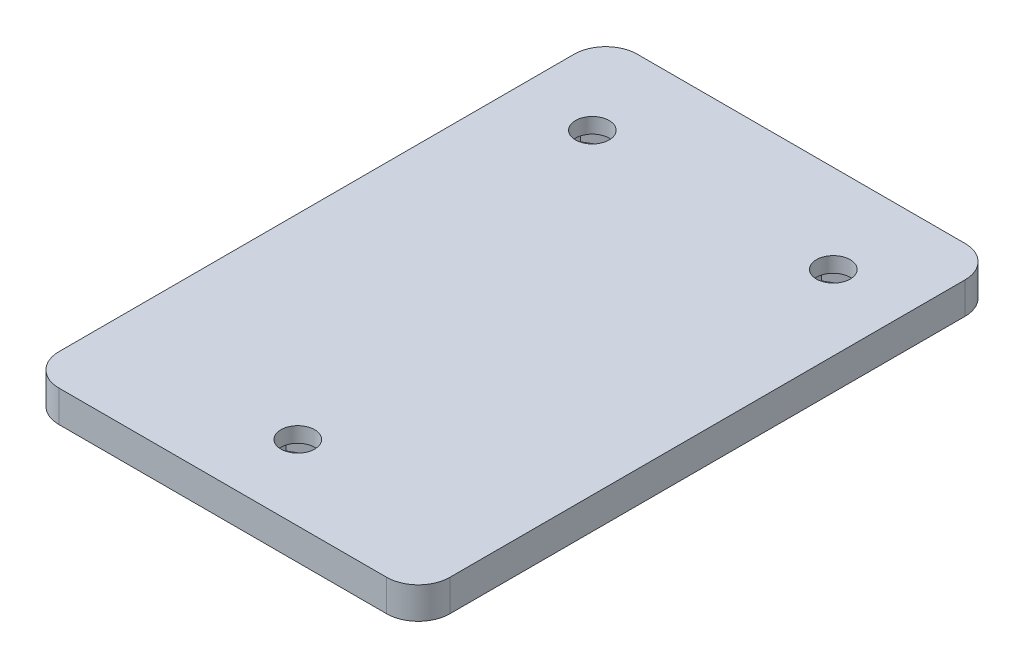
SolidWorks part; units mm, degrees
ref_plane "Front Plane" through (0, 0, 0) normal (0, 0, 1) x (1, 0, 0)
ref_plane "Top Plane" through (0, 0, 0) normal (0, 1, 0) x (1, 0, 0)
ref_plane "Right Plane" through (0, 0, 0) normal (1, 0, 0) x (0, 0, -1)
sketch "Sketch1" plane through (0, 0, 0) normal (0, 1, 0) x (1, 0, 0)
  line L1 (0, 0) -> (30.48, 0) construction
  line L2 (0, 0) -> (0, 48.26) construction
  line L3 (0, 48.26) -> (30.48, 48.26) construction
  line L4 (30.48, 0) -> (30.48, 48.26) construction
  line L8 (-0.3, -0.3) -> (-0.3, 48.56)
  line L9 (-0.3, 48.56) -> (30.78, 48.56)
  line L10 (30.78, -0.3) -> (30.78, 48.56)
  line L11 (-0.3, -0.3) -> (30.78, -0.3)
  line L12 (-3.3, -0.3) -> (-3.3, 48.56)
  line L13 (-0.3, 51.56) -> (30.78, 51.56)
  line L14 (33.78, -0.3) -> (33.78, 48.56)
  line L15 (-0.3, -3.3) -> (30.78, -3.3)
  line L16 (-3.3, -3.3) -> (-3.3, 51.56) construction
  line L17 (-3.3, -3.3) -> (33.78, -3.3) construction
  line L18 (33.78, -3.3) -> (33.78, 51.56) construction
  line L19 (-3.3, 51.56) -> (33.78, 51.56) construction
  arc A3 (-3.3, -0.3) -> (-0.3, -3.3) centre (-0.3, -0.3) ccw
  arc A4 (30.78, -3.3) -> (33.78, -0.3) centre (30.78, -0.3) ccw
  arc A5 (33.78, 48.56) -> (30.78, 51.56) centre (30.78, 48.56) ccw
  arc A6 (-0.3, 51.56) -> (-3.3, 48.56) centre (-0.3, 48.56) ccw
  dimension "D4" = 3
  dimension "D5" = 3
  dimension "D2" = 48.26
  dimension "D3" = 30.48
  dimension "D1" = 3
  dimension "D7" = 0.3
sketch "Sketch2" plane through (0, 0, 0) normal (0, 1, 0) x (1, 0, 0)
  circle A0 centre (3.81, 43.18) radius 1.6
  circle A1 centre (26.67, 43.18) radius 1.6
  circle A2 centre (15.24, 3.81) radius 1.6
  dimension "D7" = 3.2
  dimension "D8" = 3.2
  dimension "D9" = 3.2
  dimension "D1" = 3.81
  dimension "D2" = 15.24
  dimension "D3" = 43.18
  dimension "D4" = 3.81
  dimension "D5" = 43.18
  dimension "D6" = 26.67
sketch "Sketch3" plane through (0, 0, 0) normal (0, 1, 0) x (1, 0, 0)
  line L0 (15.24, 3.81) -> (15.24, 45.3871) construction
  line L10 (4.54, 9.51) -> (0.54, 9.51)
  line L11 (4.54, 9.51) -> (4.54, 23.51)
  line L12 (4.54, 23.51) -> (0.54, 23.51)
  line L13 (0.54, 9.51) -> (0.54, 23.51)
  line L14 (4.54, 9.51) -> (0.54, 23.51) construction
  line L15 (4.54, 23.51) -> (0.54, 9.51) construction
  line L16 (25.94, 23.51) -> (29.94, 9.51) construction
  line L17 (25.94, 9.51) -> (29.94, 23.51) construction
  line L18 (25.94, 23.51) -> (29.94, 23.51)
  line L19 (29.94, 9.51) -> (29.94, 23.51)
  line L20 (25.94, 9.51) -> (29.94, 9.51)
  line L21 (25.94, 9.51) -> (25.94, 23.51)
  point P0 (2.54, 16.51)
  dimension "D1" = 2.54
  dimension "D2" = 16.51
  dimension "D3" = 14
  dimension "D4" = 4
extrude "Boss-Extrude1" add sketch "Sketch1" along normal blind 3 contours L12 A6 L13 A5 L14 A4 L15 A3
extrude "Cut-Extrude4" cut sketch "Sketch2" against normal through all and the other way through all contours A0 | A1 | A2
sketch "Sketch6" plane through (0, 3, 0) normal (0, 1, 0) x (1, 0, 0)
  line L4 (-0.3, 48.56) -> (-0.3, -0.3)
  line L5 (30.78, 48.56) -> (-0.3, 48.56)
  line L6 (30.78, -0.3) -> (30.78, 48.56)
  line L7 (-0.3, -0.3) -> (30.78, -0.3)
  line L8 (-0.3, 48.56) -> (-0.3, -0.3)
  line L9 (30.78, 48.56) -> (-0.3, 48.56)
  line L10 (30.78, -0.3) -> (30.78, 48.56)
  line L11 (-0.3, -0.3) -> (30.78, -0.3)
  line L12 (-3.3, 48.56) -> (-3.3, -0.3)
  line L13 (-0.3, -3.3) -> (30.78, -3.3)
  line L14 (33.78, -0.3) -> (33.78, 48.56)
  line L15 (30.78, 51.56) -> (-0.3, 51.56)
  line L16 (-3.3, 48.56) -> (-3.3, -0.3)
  line L17 (-0.3, -3.3) -> (30.78, -3.3)
  line L18 (33.78, -0.3) -> (33.78, 48.56)
  line L19 (30.78, 51.56) -> (-0.3, 51.56)
  arc A4 (-3.3, -0.3) -> (-0.3, -3.3) centre (-0.3, -0.3) ccw
  arc A5 (30.78, -3.3) -> (33.78, -0.3) centre (30.78, -0.3) ccw
  arc A6 (33.78, 48.56) -> (30.78, 51.56) centre (30.78, 48.56) ccw
  arc A7 (-0.3, 51.56) -> (-3.3, 48.56) centre (-0.3, 48.56) ccw
  arc A8 (-3.3, -0.3) -> (-0.3, -3.3) centre (-0.3, -0.3) ccw
  arc A9 (30.78, -3.3) -> (33.78, -0.3) centre (30.78, -0.3) ccw
  arc A10 (33.78, 48.56) -> (30.78, 51.56) centre (30.78, 48.56) ccw
  arc A11 (-0.3, 51.56) -> (-3.3, 48.56) centre (-0.3, 48.56) ccw
  dimension "D1" = 0
  dimension "D2" = 0
sketch "Sketch10" plane through (0, 0, 0) normal (0, -1, 0) x (-1, 0, 0)
  line L0 (-3.81, 43.18) -> (-3.81, 29.387) construction
  line L1 (-1.21, 44.6811) -> (-3.81, 46.1822)
  line L2 (-3.81, 46.1822) -> (-6.41, 44.6811)
  line L3 (-6.41, 44.6811) -> (-6.41, 41.6789)
  line L4 (-6.41, 41.6789) -> (-3.81, 40.1778)
  line L5 (-3.81, 40.1778) -> (-1.21, 41.6789)
  line L6 (-1.21, 41.6789) -> (-1.21, 44.6811)
  line L7 (-24.07, 44.6811) -> (-26.67, 46.1822)
  line L8 (-26.67, 46.1822) -> (-29.27, 44.6811)
  line L9 (-29.27, 44.6811) -> (-29.27, 41.6789)
  line L10 (-29.27, 41.6789) -> (-26.67, 40.1778)
  line L11 (-26.67, 40.1778) -> (-24.07, 41.6789)
  line L12 (-24.07, 41.6789) -> (-24.07, 44.6811)
  line L13 (-12.64, 5.3111) -> (-15.24, 6.8122)
  line L14 (-15.24, 6.8122) -> (-17.84, 5.3111)
  line L15 (-17.84, 5.3111) -> (-17.84, 2.3089)
  line L16 (-17.84, 2.3089) -> (-15.24, 0.8078)
  line L17 (-15.24, 0.8078) -> (-12.64, 2.3089)
  line L18 (-12.64, 2.3089) -> (-12.64, 5.3111)
  line L19 (-26.67, 43.18) -> (-26.67, 34.5368)
  line L20 (-15.24, 3.81) -> (-15.24, 45.3871) construction
  circle A0 centre (-3.81, 43.18) radius 2.6 construction
  circle A1 centre (-26.67, 43.18) radius 2.6 construction
  circle A2 centre (-15.24, 3.81) radius 2.6 construction
  dimension "D1" = 5.2
  dimension "D2" = 5.2
  dimension "D3" = 5.2
extrude "Cut-Extrude8" cut sketch "Sketch10" against normal blind 1.55
